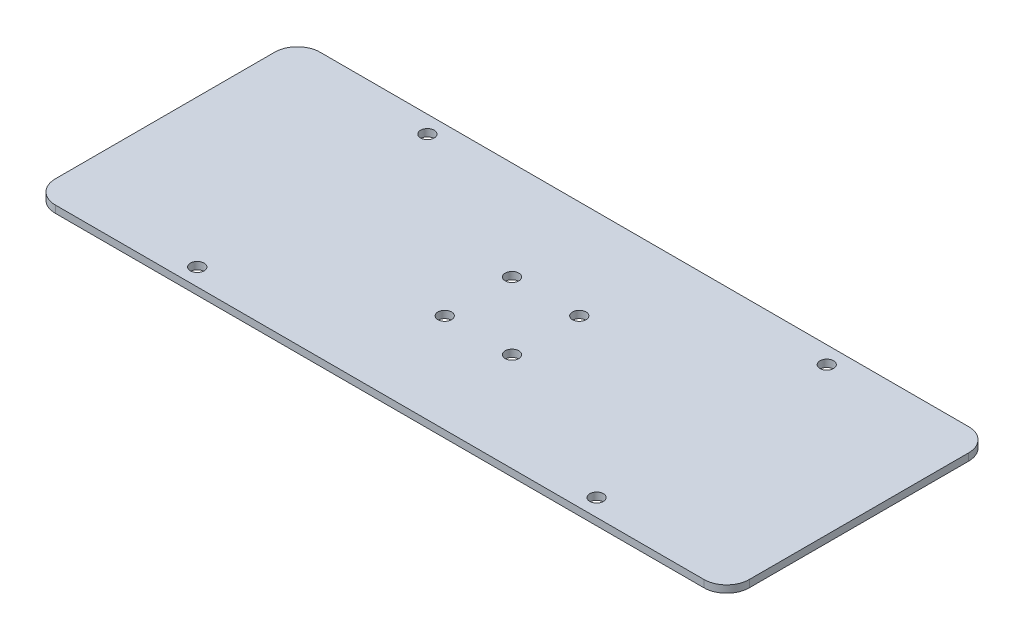
SolidWorks part; units mm, degrees
material "电源线路板"
ref_plane "前视基准面" through (0, 0, 0) normal (0, 0, 1) x (1, 0, 0)
ref_plane "上视基准面" through (0, 0, 0) normal (0, 1, 0) x (1, 0, 0)
ref_plane "右视基准面" through (0, 0, 0) normal (1, 0, 0) x (0, 0, -1)
other "Configuration Table"
sketch "草图1" plane through (0, 0, 0) normal (0, 1, 0) x (1, 0, 0)
  line L1 (-68.0661, 38.496) -> (75.0939, 38.496)
  line L2 (-73.0661, 33.496) -> (-73.0661, -14.924)
  line L3 (-68.0661, -19.924) -> (75.0939, -19.924)
  line L4 (80.0939, 33.496) -> (80.0939, -14.924)
  arc A0 (-73.0661, 33.496) -> (-68.0661, 38.496) centre (-68.0661, 33.496) cw
  arc A1 (80.0939, 33.496) -> (75.0939, 38.496) centre (75.0939, 33.496) ccw
  arc A2 (75.0939, -19.924) -> (80.0939, -14.924) centre (75.0939, -14.924) ccw
  arc A3 (-73.0661, -14.924) -> (-68.0661, -19.924) centre (-68.0661, -14.924) ccw
  circle A4 centre (-40.5561, 34.686) radius 1.5
  circle A5 centre (-40.5561, -16.114) radius 1.5
  circle A6 centre (47.5839, 34.686) radius 1.5
  circle A7 centre (47.5839, -16.114) radius 1.5
  circle A8 centre (-3.9103, 16.711) radius 1.5
  circle A11 centre (10.9382, 1.861) radius 1.5
  circle A13 centre (10.9397, 16.711) radius 1.5
  circle A14 centre (-3.9118, 1.864) radius 1.5
  point P6 (-73.0661, 38.496)
  point P9 (80.0939, 38.496)
  point P12 (80.0939, -19.924)
  dimension "D3" = 5
  dimension "D4" = 5
  dimension "D5" = 5
  dimension "D6" = 5
  dimension "D7" = 88.14
  dimension "D15" = 14.85
  dimension "D16" = 14.85
  dimension "D21" = 21
  dimension "D22" = 0
  dimension "D1" = 153.16
  dimension "D2" = 58.42
  dimension "D8" = 0
  dimension "D9" = 50.8
  dimension "D10" = 88.14
  dimension "D11" = 50.8
  dimension "D12" = 0
  dimension "D13" = 3.81
  dimension "D14" = 32.51
  dimension "D17" = 14.847
  dimension "D18" = 21
  dimension "D23" = 3.81
  dimension "D24" = 14.85
extrude "凸台-拉伸1" add sketch "草图1" along normal blind 1.6
